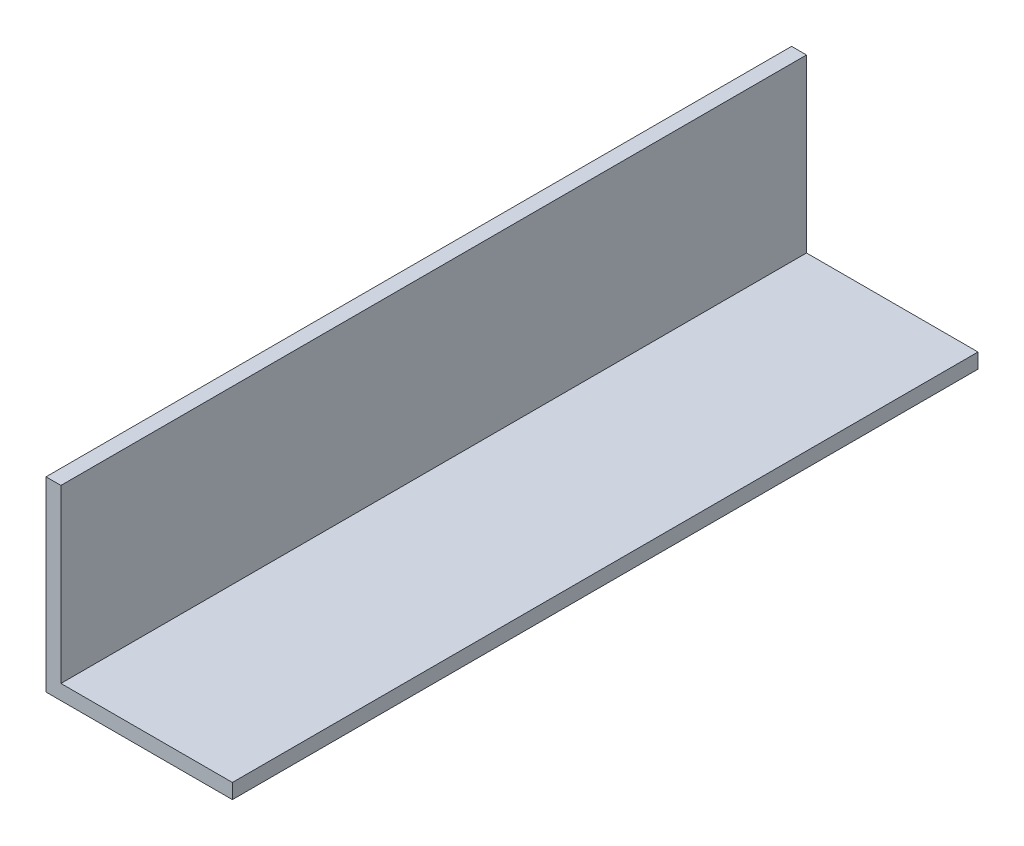
SolidWorks part; units mm, degrees
ref_plane "Front Plane" through (0, 0, 0) normal (0, 0, 1) x (1, 0, 0)
ref_plane "Top Plane" through (0, 0, 0) normal (0, 1, 0) x (1, 0, 0)
ref_plane "Right Plane" through (0, 0, 0) normal (1, 0, 0) x (0, 0, -1)
sketch "Sketch1" plane through (0, 0, 0) normal (0, 0, 1) x (1, 0, 0)
  line L0 (0, 0) -> (25, 0)
  line L1 (25, 0) -> (25, 2)
  line L2 (25, 2) -> (2, 2)
  line L3 (2, 2) -> (2, 25)
  line L4 (2, 25) -> (0, 25)
  line L5 (0, 25) -> (0, 0)
  dimension "D1" = 25
  dimension "D2" = 25
  dimension "D3" = 2
  dimension "D4" = 2
extrude "Boss-Extrude1" add sketch "Sketch1" along normal blind 100
